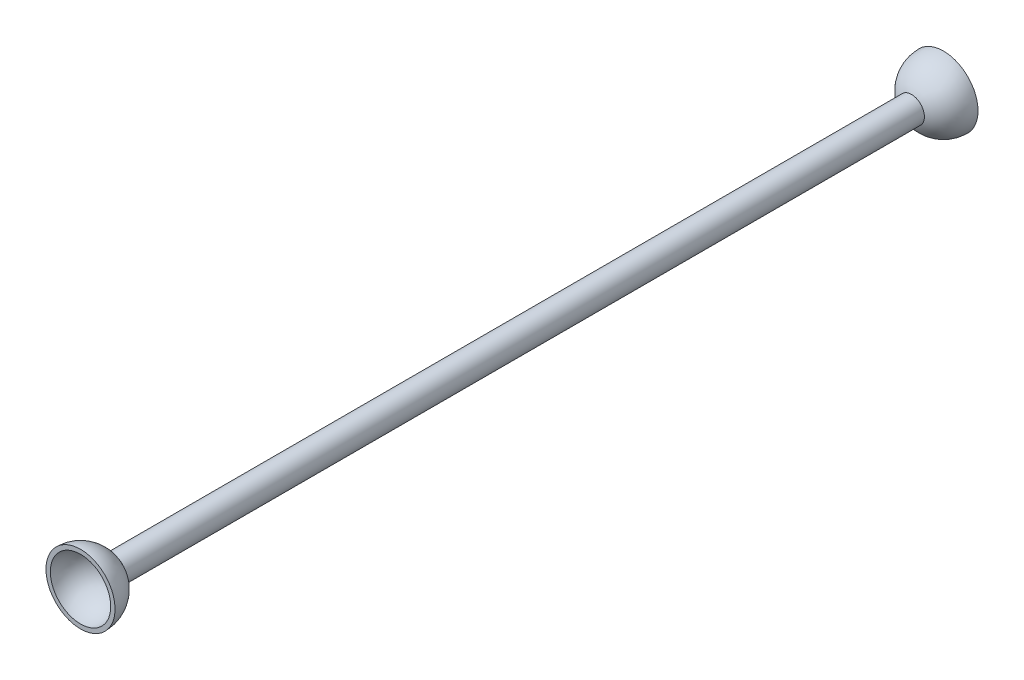
SolidWorks part; units mm, degrees
ref_plane "Front" through (0, 0, 0) normal (0, 0, 1) x (1, 0, 0)
ref_plane "Top" through (0, 0, 0) normal (0, 1, 0) x (1, 0, 0)
ref_plane "Right" through (0, 0, 0) normal (1, 0, 0) x (0, 0, -1)
sketch "Sketch1" plane through (0, 0, 0) normal (0, 0, 1) x (1, 0, 0)
  circle A0 centre (0, 0) radius 3
extrude "Boss-Extrude1" add sketch "Sketch1" along normal blind 200
sketch "Sketch2" plane through (0, 0, 200) normal (0, 0, 1) x (1, 0, 0)
  line L0 (0, 8) -> (0, 7)
  line L1 (0, -7) -> (0, -8)
  line L2 (0, 7) -> (0, -7)
  arc A1 (0, -8) -> (0, 8) centre (0, 0) ccw
revolve "Revolve1" add sketch "Sketch2" angle 180 about L0
sketch "Sketch3" plane through (0, 0, 200) normal (0, 0, 1) x (1, 0, 0)
  line L0 (0, 7) -> (0, -7)
  arc A0 (0, -7) -> (0, 7) centre (0, 0) ccw
revolve "Cut-Revolve1" cut sketch "Sketch3" angle 360 about L0
sketch "Sketch4" plane through (0, 0, 0) normal (0, 0, -1) x (-1, 0, 0)
  line L0 (0, 8) -> (0, -8)
  arc A0 (0, -8) -> (0, 8) centre (0, 0) ccw
revolve "Revolve2" add sketch "Sketch4" angle 180 about L0
sketch "Sketch5" plane through (0, 0, 0) normal (0, 0, -1) x (-1, 0, 0)
  line L0 (0, 7) -> (0, -7)
  arc A0 (0, -7) -> (0, 7) centre (0, 0) ccw
revolve "Cut-Revolve2" cut sketch "Sketch5" angle 360 about L0
